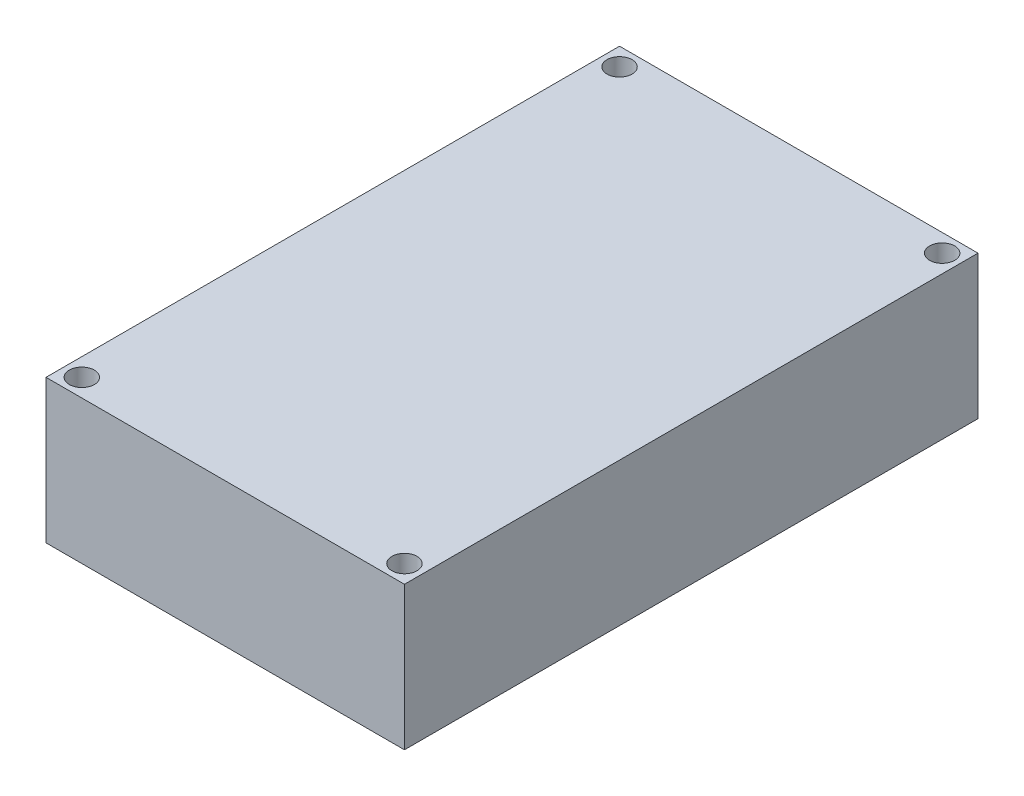
SolidWorks part; units mm, degrees
ref_plane "Front Plane" through (0, 0, 0) normal (0, 0, 1) x (1, 0, 0)
ref_plane "Top Plane" through (0, 0, 0) normal (0, 1, 0) x (1, 0, 0)
ref_plane "Right Plane" through (0, 0, 0) normal (1, 0, 0) x (0, 0, -1)
sketch "Sketch1" plane through (0, 0, 0) normal (0, 1, 0) x (1, 0, 0)
  line L1 (-6.5594, 22.8968) -> (43.4406, 22.8968)
  line L2 (-6.5594, 22.8968) -> (-6.5594, -57.1032)
  line L3 (-6.5594, -57.1032) -> (43.4406, -57.1032)
  line L4 (43.4406, 22.8968) -> (43.4406, -57.1032)
  circle A0 centre (40.9406, 20.3968) radius 1.75
  circle A1 centre (-4.0594, 20.3968) radius 1.75
  circle A2 centre (-4.0594, -54.6032) radius 1.75
  circle A3 centre (40.9406, -54.6032) radius 1.75
  dimension "D3" = 3.5
  dimension "D6" = 2.5
  dimension "D7" = 2.5
  dimension "D1" = 80
  dimension "D2" = 50
  dimension "D4" = 2.5
  dimension "D5" = 2.5
extrude "Boss-Extrude1" add sketch "Sketch1" along normal blind 20
